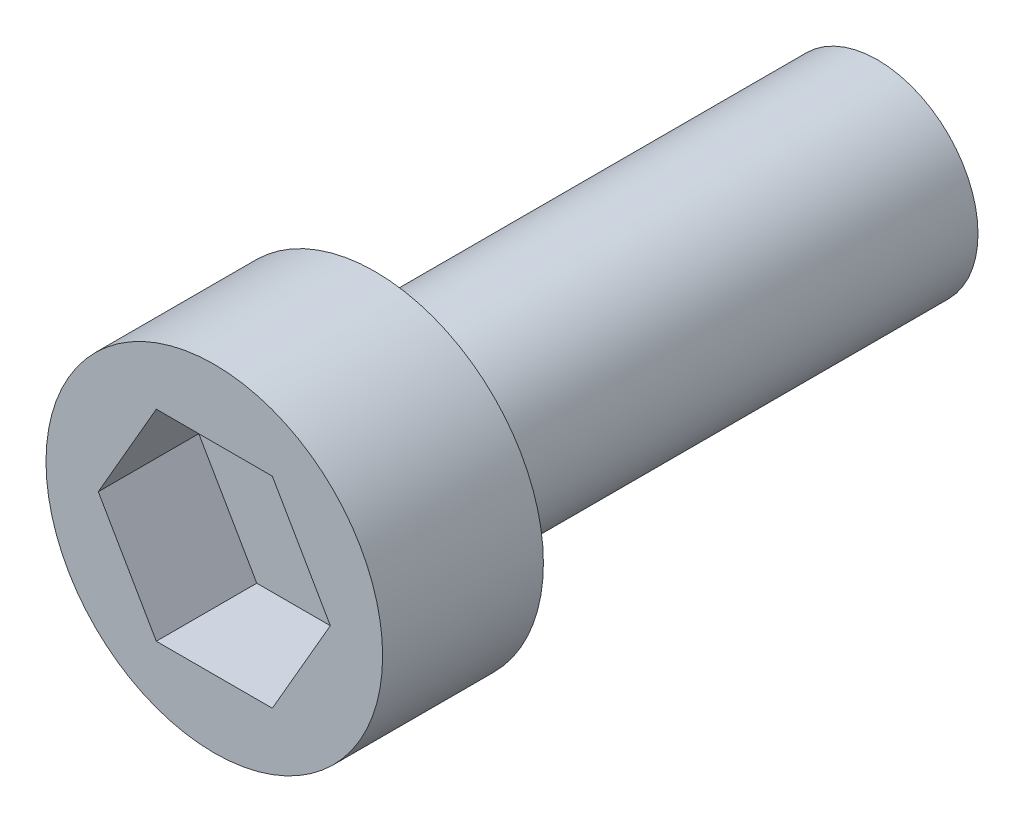
SolidWorks part; units mm, degrees
ref_plane "Plan de face" through (0, 0, 0) normal (0, 0, 1) x (1, 0, 0)
ref_plane "Plan de dessus" through (0, 0, 0) normal (0, 1, 0) x (1, 0, 0)
ref_plane "Plan de droite" through (0, 0, 0) normal (1, 0, 0) x (0, 0, -1)
sketch "Esquisse1" plane through (0, 0, 0) normal (0, 0, 1) x (1, 0, 0)
  circle A0 centre (0, 0) radius 1
  dimension "D1" = 2
extrude "Boss.-Extru.1" add sketch "Esquisse1" along normal blind 5
sketch "Esquisse2" plane through (0, 0, 5) normal (0, 0, 1) x (1, 0, 0)
  circle A0 centre (0, 0) radius 1.675
  dimension "D1" = 3.35
extrude "Boss.-Extru.2" add sketch "Esquisse2" along normal blind 1.6
sketch "Esquisse3" plane through (0, 0, 6.6) normal (0, 0, 1) x (1, 0, 0)
  line L1 (1.1547, 0) -> (0.5774, 1)
  line L2 (0.5774, 1) -> (-0.5774, 1)
  line L3 (-0.5774, 1) -> (-1.1547, 0)
  line L4 (-1.1547, 0) -> (-0.5774, -1)
  line L5 (-0.5774, -1) -> (0.5774, -1)
  line L6 (0.5774, -1) -> (1.1547, 0)
  circle A0 centre (0, 0) radius 1 construction
  dimension "D1" = 2
extrude "Enlèv. mat.-Extru.1" cut sketch "Esquisse3" against normal blind 1
